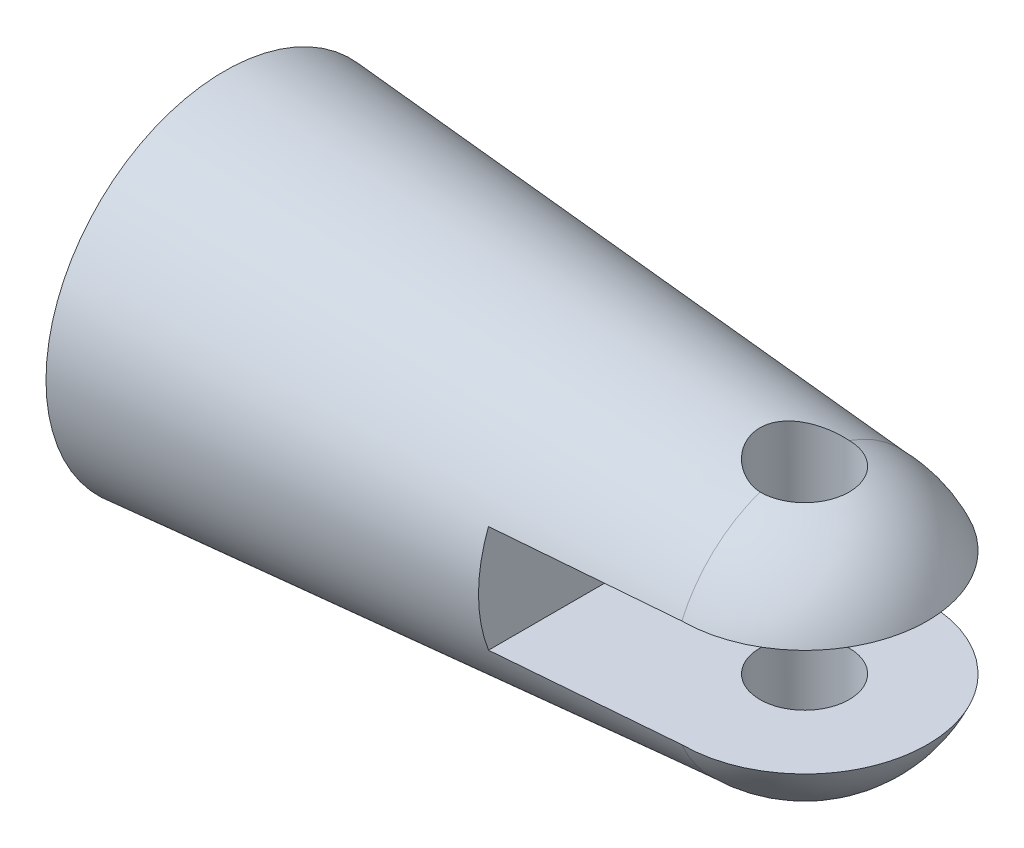
SolidWorks part; units mm, degrees
ref_plane "Ön Düzlem" through (0, 0, 0) normal (0, 0, 1) x (1, 0, 0)
ref_plane "Üst Düzlem" through (0, 0, 0) normal (0, 1, 0) x (1, 0, 0)
ref_plane "Sağ Düzlem" through (0, 0, 0) normal (1, 0, 0) x (0, 0, -1)
sketch "Sketch1" plane through (0, 0, 0) normal (0, 1, 0) x (1, 0, 0)
  line L0 (0, 0) -> (0, 20)
  line L1 (0, 20) -> (65, 15)
  line L2 (-20.9083, 0) -> (89.6435, 0) construction
  line L3 (0, 0) -> (80, 0)
  arc A0 (80, 0) -> (65, 15) centre (65, 0) ccw
  dimension "D1" = 65
  dimension "D2" = 20
  dimension "D3" = 15
revolve "Revolve1" add sketch "Sketch1" angle 360 about L2
sketch "Sketch2" plane through (0, 0, 0) normal (0, 1, 0) x (1, 0, 0)
  line L0 (65, -15) -> (65, 15) construction
  circle A0 centre (65, 0) radius 5
extrude "Cut-Extrude1" cut sketch "Sketch2" against normal mid plane 50
sketch "Sketch3" plane through (0, 0, 0) normal (-1, 0, 0) x (0, 0, 1)
  circle A0 centre (0, 0) radius 8
extrude "Boss-Extrude1" add sketch "Sketch3" along normal blind 8
sketch "Sketch4" plane through (0, 0, 0) normal (0, 0, 1) x (1, 0, 0)
  line L0 (65, -14.1421) -> (65, 14.1421) construction
  line L1 (45, 6) -> (85, 6)
  line L2 (45, 6) -> (45, -6)
  line L3 (45, -6) -> (85, -6)
  line L4 (85, 6) -> (85, -6)
  line L5 (45, 6) -> (85, -6) construction
  line L6 (45, -6) -> (85, 6) construction
  point P0 (65, 0)
  dimension "D1" = 20
  dimension "D2" = 12
extrude "Cut-Extrude2" cut sketch "Sketch4" against normal mid plane 40
